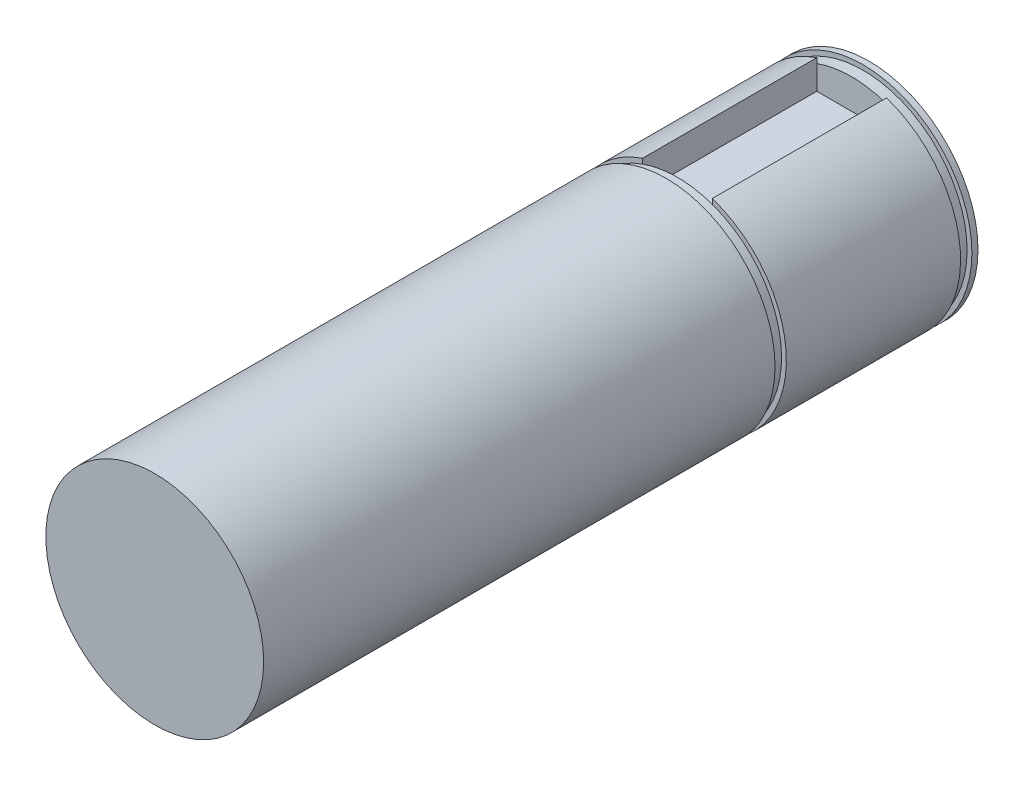
SolidWorks part; units mm, degrees
ref_plane "Front Plane" through (0, 0, 0) normal (0, 0, 1) x (1, 0, 0)
ref_plane "Top Plane" through (0, 0, 0) normal (0, 1, 0) x (1, 0, 0)
ref_plane "Right Plane" through (0, 0, 0) normal (1, 0, 0) x (0, 0, -1)
sketch "Sketch1" plane through (0, 0, 0) normal (0, 0, 1) x (1, 0, 0)
  circle A0 centre (0, 0) radius 12.5
  dimension "D1" = 25
extrude "Boss-Extrude1" add sketch "Sketch1" along normal blind 80 and the other way blind 2
sketch "Sketch2" plane through (0, 0, -2) normal (0, 0, -1) x (-1, 0, 0)
  line L4 (-4, 11.8427) -> (-4, 8.5)
  line L9 (-4, 8.5) -> (4, 8.5)
  line L10 (4, 8.5) -> (4, 11.8427)
  circle A1 centre (0, 0) radius 12.5 construction
  arc A2 (-4, 11.8427) -> (4, 11.8427) centre (0, 0) cw
  dimension "D1" = 4
  dimension "D2" = 8
extrude "Cut-Extrude1" cut sketch "Sketch2" against normal blind 20 from offset 2 offset against normal yes
sketch "Sketch4" plane through (0, 0, 0) normal (1, 0, 0) x (0, 0, -1)
  line L0 (2, 12.5) -> (0, 12.5) construction
  line L1 (0, 12.5) -> (1.3, 12.5)
  line L2 (0, 12.5) -> (0, 11.95)
  line L3 (0, 11.95) -> (1.3, 11.95)
  line L4 (1.3, 12.5) -> (1.3, 11.95)
  line L5 (0, 12.5) -> (0, 11.8427) construction
  line L7 (5.5663, 0) -> (-83.6311, 0) construction
  dimension "D1" = 1.3
  dimension "D2" = 0.55
revolve "Cut-Revolve1" cut sketch "Sketch4" angle 360 about L7
sketch "Sketch5" plane through (0, 0, 0) normal (1, 0, 0) x (0, 0, -1)
  line L0 (-20, 11.8427) -> (-20, 12.5) construction
  line L1 (-20, 12.5) -> (-21.3, 12.5)
  line L2 (-20, 12.5) -> (-20, 11.95)
  line L3 (-20, 11.95) -> (-21.3, 11.95)
  line L4 (-21.3, 12.5) -> (-21.3, 11.95)
  line L5 (0, 0) -> (-80, 0) construction
  line L7 (-80, 12.5) -> (-80, -12.5) construction
  point P6 (-80, 0)
  dimension "D1" = 0.55
  dimension "D2" = 1.3
  dimension "D3" = 12.5
revolve "Cut-Revolve2" cut sketch "Sketch5" angle 360 about L5
